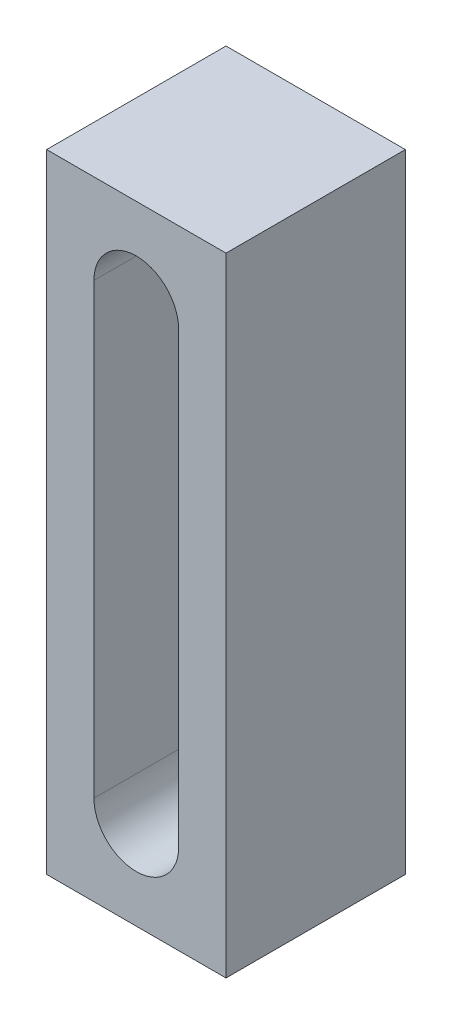
SolidWorks part; units mm, degrees
ref_plane "Front Plane" through (0, 0, 0) normal (0, 0, 1) x (1, 0, 0)
ref_plane "Top Plane" through (0, 0, 0) normal (0, 1, 0) x (1, 0, 0)
ref_plane "Right Plane" through (0, 0, 0) normal (1, 0, 0) x (0, 0, -1)
sketch "Sketch1" plane through (0, 0, 0) normal (0, 0, 1) x (1, 0, 0)
  line L0 (0, -7.9375) -> (0, 7.9375) construction
  line L1 (-1.5, -7.9375) -> (-1.5, 7.9375)
  line L2 (1.5, -7.9375) -> (1.5, 7.9375)
  line L4 (3.175, -11.1125) -> (-3.175, -11.1125)
  line L5 (3.175, -11.1125) -> (3.175, 11.1125)
  line L6 (3.175, 11.1125) -> (-3.175, 11.1125)
  line L7 (-3.175, -11.1125) -> (-3.175, 11.1125)
  line L8 (3.175, -11.1125) -> (-3.175, 11.1125) construction
  line L9 (3.175, 11.1125) -> (-3.175, -11.1125) construction
  arc A0 (-1.5, -7.9375) -> (1.5, -7.9375) centre (0, -7.9375) ccw
  arc A1 (1.5, 7.9375) -> (-1.5, 7.9375) centre (0, 7.9375) ccw
  point P2 (0, 0)
  point P7 (0, 0)
  point P12 (1.469, 9.5924)
  point P13 (0, 0)
  dimension "D4" = 1.5
  dimension "D1" = 6.35
  dimension "D2" = 22.225
  dimension "D3" = 15.875
extrude "Boss-Extrude1" add sketch "Sketch1" along normal mid plane 6.35
